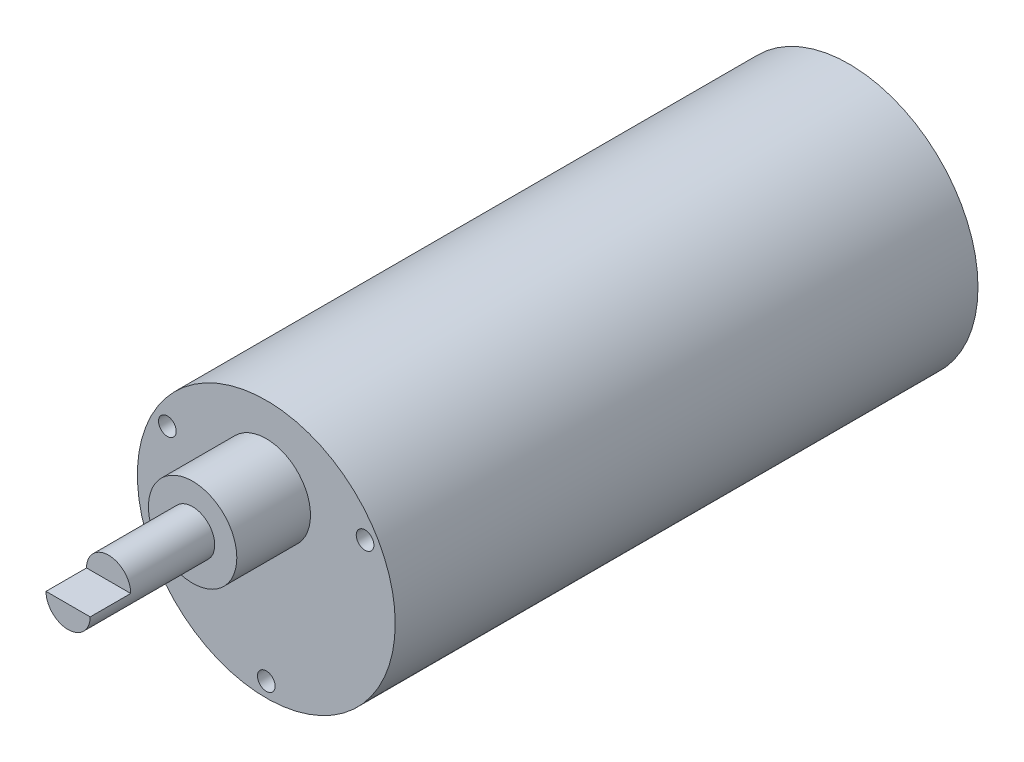
SolidWorks part; units mm, degrees
ref_plane "Plan de dos" through (0, 0, 0) normal (0, 0, 1) x (1, 0, 0)
ref_plane "Plan de dessus" through (0, 0, 0) normal (0, 1, 0) x (1, 0, 0)
ref_plane "Plan de droite" through (0, 0, 0) normal (1, 0, 0) x (0, 0, -1)
sketch "Esquisse1" plane through (0, 0, 0) normal (0, 0, 1) x (1, 0, 0)
  circle A0 centre (0, 0) radius 17.5
extrude "Boss.-Extru.1" add sketch "Esquisse1" along normal blind 79.1
sketch "Esquisse2" plane through (0, 0, 79.1) normal (0, 0, 1) x (1, 0, 0)
  line L0 (0, 0) -> (0, 7) construction
  circle A0 centre (0, 7) radius 6
extrude "Boss.-Extru.2" add sketch "Esquisse2" along normal blind 10
sketch "Esquisse3" plane through (0, 0, 89.1) normal (0, 0, 1) x (1, 0, 0)
  line L0 (3.6955, 11.7269) -> (0, 7) construction
  circle A0 centre (0, 7) radius 6 construction
  circle A1 centre (0, 7) radius 3
extrude "Boss.-Extru.3" add sketch "Esquisse3" along normal blind 16.9
sketch "Esquisse4" plane through (0, 0, 106) normal (0, 0, 1) x (1, 0, 0)
  line L1 (-3, 10) -> (3, 10)
  line L2 (-3, 10) -> (-3, 7)
  line L3 (-3, 7) -> (3, 7)
  line L4 (3, 10) -> (3, 7)
  circle A0 centre (0, 7) radius 3 construction
  circle A1 centre (0, 7) radius 3 construction
extrude "Enlèv. mat.-Extru.1" cut sketch "Esquisse4" against normal blind 5.5
sketch "Esquisse8" plane through (0, 0, 79.1) normal (0, 0, 1) x (1, 0, 0)
  line L0 (17.5, 0) -> (-17.5, 0) construction
  line L1 (0, 0) -> (0, -17.5) construction
  line L2 (0, 0) -> (-15.1554, 8.75) construction
  line L3 (0, 0) -> (15.1554, 8.75) construction
  circle A0 centre (0, 0) radius 17.5 construction
  circle A1 centre (0, 0) radius 15.5
  point P10 (0, -15.5)
  point P11 (13.4064, 7.7794)
  point P12 (-13.4234, 7.75)
hole_wizard "Dégagement M24" positions "Esquisse3D2" profile "Esquisse12" hole size "M2" standard "ISO"
sketch3d "Esquisse3D2"
  point P0 (13.4064, 7.7794, 79.1)
  point P3 (0, -15.5, 79.1)
  point P6 (-13.4234, 7.75, 79.1)
sketch "Esquisse12" plane through (13.4064, 7.7794, 79.1) normal (1, 0, 0) x (0, -1, 0)
  line L0 (0, 0) -> (0, 10.721)
  line L1 (0, 10.721) -> (1.2, 10)
  line L2 (1.2, 10) -> (1.2, 0)
  line L5 (1.2, 0) -> (0, 0)
  line L10 (0, 10.721) -> (-1.2, 10) construction
  line L11 (0, -6.35) -> (0, 107.95) construction
  dimension "Diamètre du perçage" = 2.4
  dimension "Profondeur du perçage" = 10
  dimension "Angle de pointe" = 118
